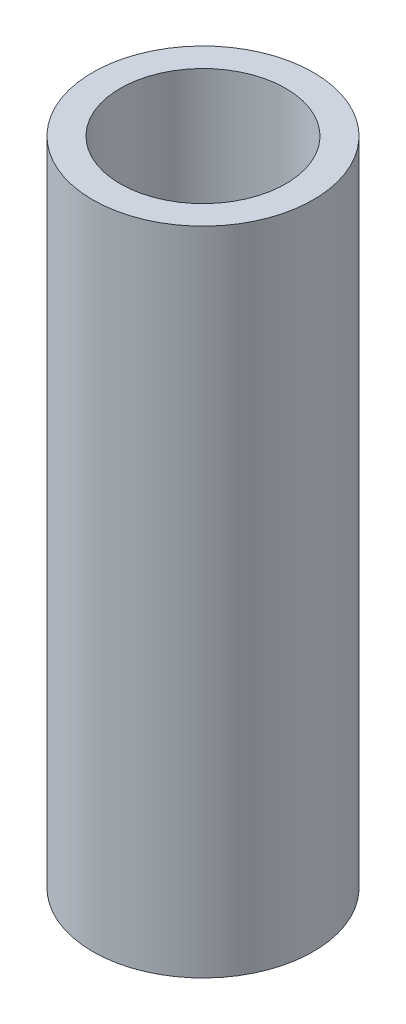
SolidWorks part; units mm, degrees
material "304 Stainless Steel"
ref_plane "Front Plane" through (0, 0, 0) normal (0, 0, 1) x (1, 0, 0)
ref_plane "Top Plane" through (0, 0, 0) normal (0, 1, 0) x (1, 0, 0)
ref_plane "Right Plane" through (0, 0, 0) normal (1, 0, 0) x (0, 0, -1)
sketch "Sketch1" plane through (0, 0, 0) normal (0, 1, 0) x (1, 0, 0)
  circle A0 centre (0, 0) radius 10
  circle A1 centre (0, 0) radius 7.5
  dimension "D1" = 20
  dimension "D2" = 2.5
extrude "Extrude1" add sketch "Sketch1" along normal blind 59
